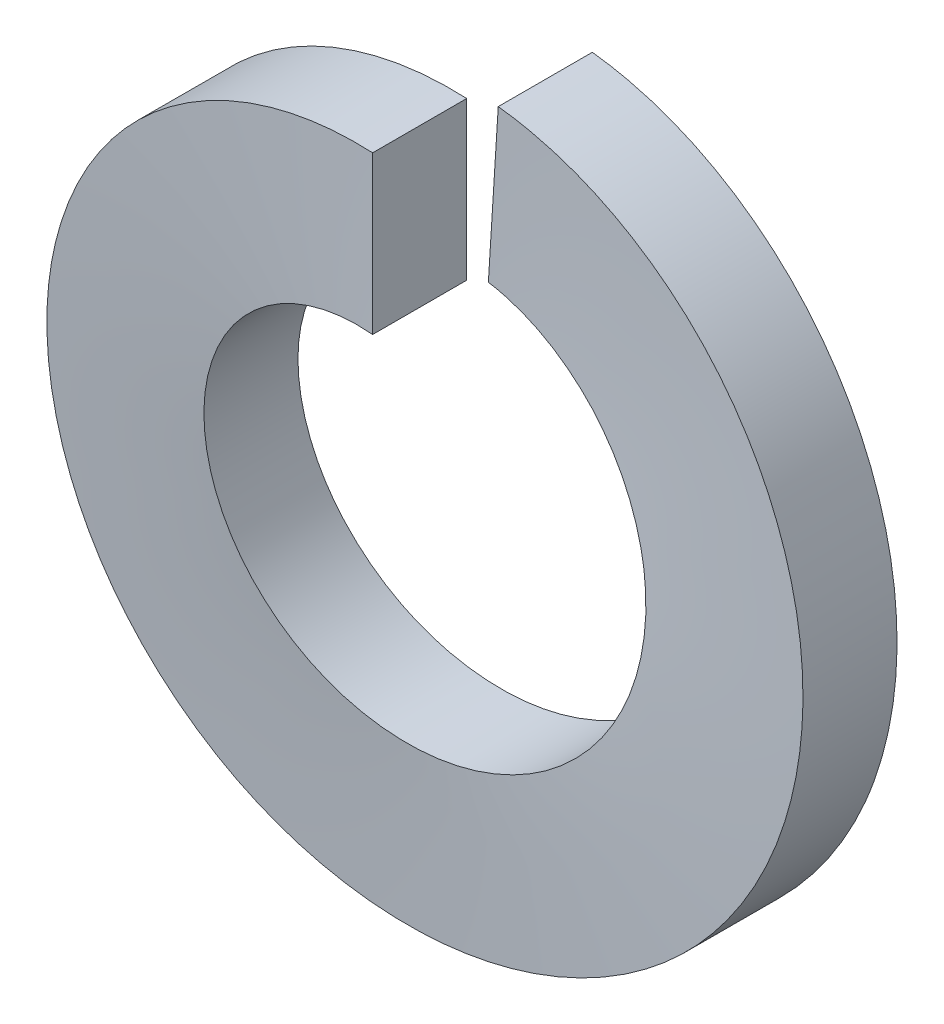
SolidWorks part; units mm, degrees
ref_plane "Front Plane" through (0, 0, 0) normal (0, 0, 1) x (1, 0, 0)
ref_plane "Top Plane" through (0, 0, 0) normal (0, 1, 0) x (1, 0, 0)
ref_plane "Right Plane" through (0, 0, 0) normal (1, 0, 0) x (0, 0, -1)
sketch "Sketch1" plane through (0, 0, 0) normal (0, 0, 1) x (1, 0, 0)
  line L0 (0, 7.4041) -> (0, 4.0894) construction
  circle A0 centre (0, 0) radius 7.4041
  circle A1 centre (0, 0) radius 4.0894 construction
  dimension "ID" = 8.1788
  dimension "OD" = 14.8082
curve "Helix/Spiral1" pitch 2.2013 height 2.1793 turns 0.99 parameters "HT"=2.1793
sketch "Sketch2" plane through (0, 0, 0) normal (1, 0, 0) x (0, 0, -1)
  line L1 (0, 7.4041) -> (-1.9812, 7.4041)
  line L2 (0, 7.4041) -> (0, 4.0894)
  line L3 (0, 4.0894) -> (-1.9812, 4.0894)
  line L4 (-1.9812, 7.4041) -> (-1.9812, 4.0894)
  dimension "THK" = 1.9812
sweep "Sweep1" add profiles "Sketch2" path "Helix/Spiral1"
equation "\"HT@Helix/Spiral1\" = \"THK@Sketch2\"*1.1"
